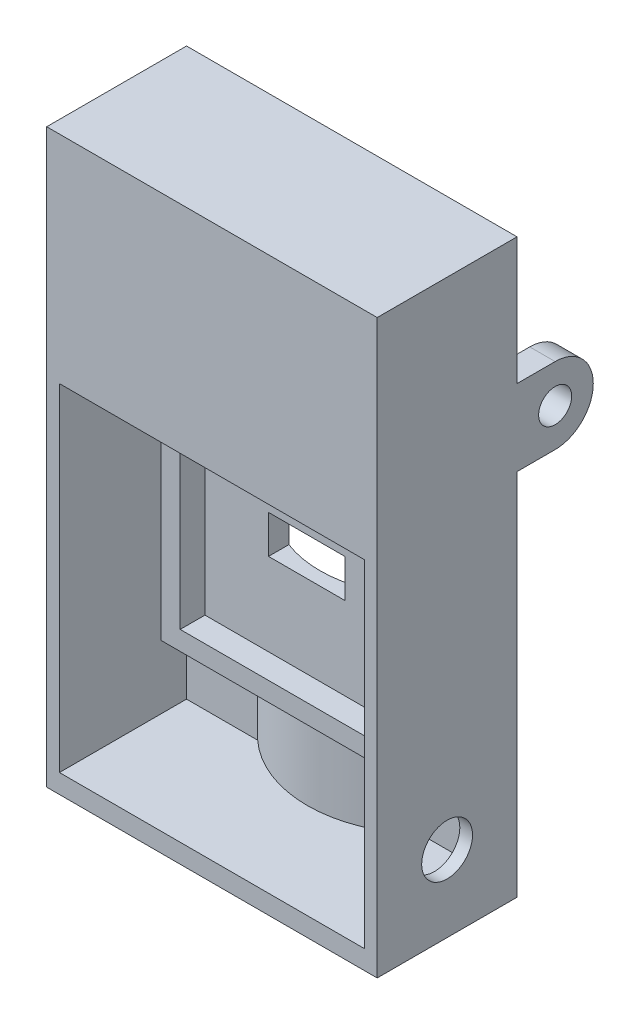
SolidWorks part; units mm, degrees
ref_plane "Front Plane" through (0, 0, 0) normal (0, 0, 1) x (1, 0, 0)
ref_plane "Top Plane" through (0, 0, 0) normal (0, 1, 0) x (1, 0, 0)
ref_plane "Right Plane" through (0, 0, 0) normal (1, 0, 0) x (0, 0, -1)
sketch "Sketch1" plane through (0, 0, 0) normal (0, 0, 1) x (1, 0, 0)
  line L1 (0, 0) -> (26, 0)
  line L2 (0, 0) -> (0, -45)
  line L3 (0, -45) -> (26, -45)
  line L4 (26, 0) -> (26, -45)
  dimension "D1" = 45
  dimension "D2" = 26
extrude "Boss-Extrude1" add sketch "Sketch1" along normal blind 11
sketch "Sketch2" plane through (0, -45, 0) normal (0, -1, 0) x (1, 0, 0)
  line L0 (0, 0) -> (26, 0) construction
  line L1 (7, 0) -> (19, 0) construction
  line L2 (13, 2.5) -> (13, 0) construction
  circle A0 centre (13, -5.95) radius 8.45
  point P5 (13, 0)
  dimension "D1" = 2.5
  dimension "D2" = 12
extrude "Cut-Extrude1" cut sketch "Sketch2" against normal blind 28
ref_plane "Plane1" through (0, -43.5, 0) normal (0, -1, 0) x (-1, 0, 0)
sketch "Sketch4" plane through (0, -43.5, 0) normal (0, -1, 0) x (-1, 0, 0)
  line L0 (-1, -11) -> (-1, -1)
  line L1 (-1, -1) -> (-6.5969, -1)
  line L2 (-19.4031, -1) -> (-25, -1)
  line L3 (-25, -1) -> (-25, -11)
  line L4 (-1, -11) -> (-25, -11)
  line L5 (0, 0) -> (-7, 0)
  line L6 (-19, 0) -> (-26, 0)
  line L7 (-26, 0) -> (-26, -11)
  line L8 (-26, -11) -> (0, -11)
  line L9 (0, -11) -> (0, 0)
  line L10 (0, 0) -> (-7, 0) construction
  line L11 (-19, 0) -> (-26, 0) construction
  line L12 (-26, 0) -> (-26, -11) construction
  line L13 (-26, -11) -> (0, -11) construction
  line L14 (0, -11) -> (0, 0) construction
  arc A0 (-19.4031, -1) -> (-6.5969, -1) centre (-13, 5.95) ccw
  arc A1 (-19, 0) -> (-7, 0) centre (-13, 5.95) ccw
  arc A2 (-19, 0) -> (-7, 0) centre (-13, 5.95) ccw construction
  dimension "D1" = 0
  dimension "D2" = 1
extrude "Cut-Extrude2" cut sketch "Sketch4" against normal blind 26.5
ref_plane "Plane2" through (0, 0, 3.5) normal (0, 0, 1) x (1, 0, 0)
sketch "Sketch5" plane through (0, 0, 3.5) normal (0, 0, 1) x (1, 0, 0)
  line L0 (25, -17) -> (1, -17) construction
  line L1 (5, -18.5) -> (21, -18.5) construction
  line L2 (5, -18.5) -> (5, -34.5) construction
  line L3 (5, -34.5) -> (21, -34.5) construction
  line L4 (21, -18.5) -> (21, -34.5) construction
  line L5 (0, -45) -> (26, -45) construction
  line L7 (10, -25) -> (16, -25)
  line L8 (10, -25) -> (10, -28)
  line L9 (10, -28) -> (16, -28)
  line L10 (16, -25) -> (16, -28)
  point P6 (13, -34.5)
  point P9 (13, -45)
  point P14 (13, -25)
  point P15 (13, -18.5)
  point P16 (10, -26.5)
  point P17 (5, -26.5)
  dimension "D1" = 16
  dimension "D2" = 1.5
  dimension "D3" = 6
  dimension "D4" = 3
extrude "Cut-Extrude3" cut sketch "Sketch5" against normal through all
sketch "Sketch6" plane through (0, -17, 0) normal (0, -1, 0) x (1, 0, 0)
  line L0 (6.5969, 1) -> (3.5, 1)
  line L1 (1, 1) -> (6.5969, 1) construction
  line L2 (3.5, 1) -> (3.5, 5.5)
  line L3 (3.5, 5.5) -> (22.5, 5.5)
  line L4 (22.5, 5.5) -> (22.5, 1)
  line L5 (19.4031, 1) -> (25, 1) construction
  line L6 (22.5, 1) -> (19.4031, 1)
  line L7 (25, 11) -> (1, 11) construction
  arc A0 (19.4031, 1) -> (6.5969, 1) centre (13, -5.95) ccw construction
  arc A1 (19.4031, 1) -> (6.5969, 1) centre (13, -5.95) ccw
  point P3 (13, 5.5)
  point P14 (13, 11)
  dimension "D1" = 19
  dimension "D2" = 4.5
extrude "Boss-Extrude4" add sketch "Sketch6" along normal blind 19
sketch "Sketch8" plane through (0, 0, 5.5) normal (0, 0, 1) x (1, 0, 0)
  line L5 (5, -18.5) -> (21, -18.5) construction
  line L6 (21, -18.5) -> (21, -34.5) construction
  line L7 (5, -34.5) -> (21, -34.5) construction
  line L8 (5, -18.5) -> (5, -34.5) construction
  line L9 (5, -18.5) -> (21, -18.5)
  line L10 (21, -18.5) -> (21, -34.5)
  line L11 (5, -34.5) -> (21, -34.5)
  line L12 (5, -18.5) -> (5, -34.5)
extrude "Cut-Extrude7" cut sketch "Sketch8" against normal blind 1.95
sketch "Sketch9" plane through (0, 0, 3.55) normal (0, 0, 1) x (1, 0, 0)
  line L0 (10, -28) -> (16, -28) construction
  line L1 (10, -28) -> (16, -28)
  line L2 (10, -25) -> (10, -28) construction
  line L3 (10, -25) -> (10, -28)
  line L4 (16, -25) -> (16, -28) construction
  line L5 (16, -25) -> (16, -28)
  line L6 (10, -25) -> (16, -25) construction
  line L7 (10, -25) -> (16, -25)
extrude "Cut-Extrude8" cut sketch "Sketch9" against normal through all
sketch "Sketch10" plane through (26, 0, 0) normal (1, 0, 0) x (0, 0, -1)
  line L0 (-11, -45) -> (0, -45) construction
  circle A0 centre (-5.5, -39) radius 2
  point P5 (-5.5, -45)
  dimension "D2" = 4
  dimension "D1" = 6
extrude "Cut-Extrude9" cut sketch "Sketch10" against normal blind 4
sketch "Sketch11" plane through (26, 0, 0) normal (1, 0, 0) x (0, 0, -1)
  line L5 (0, -10) -> (3, -10)
  line L6 (0, -45) -> (0, 0) construction
  line L7 (3, -16) -> (0, -16)
  line L8 (0, -16) -> (0, -10)
  arc A3 (3, -10) -> (3, -16) centre (3, -13) cw
  circle A4 centre (3, -13) radius 1.3
  dimension "D3" = 4
  dimension "D4" = 2.6
  dimension "D1" = 3
  dimension "D2" = 6
extrude "Boss-Extrude5" add sketch "Sketch11" against normal up to surface (26 mm away) up to face at (0, -22.5, 5.5)
sketch "Sketch13" plane through (0, 0, 0) normal (0, 0, -1) x (-1, 0, 0)
  line L1 (-2, -18.1661) -> (-24, -18.1661)
  line L2 (-2, -18.1661) -> (-2, -5.3738)
  line L3 (-2, -5.3738) -> (-24, -5.3738)
  line L4 (-24, -18.1661) -> (-24, -5.3738)
  line L5 (0, -16) -> (0, -45) construction
  line L6 (-26, -45) -> (-26, -16) construction
  dimension "D1" = 2
  dimension "D2" = 2
extrude "Cut-Extrude11" cut sketch "Sketch13" along normal through all
